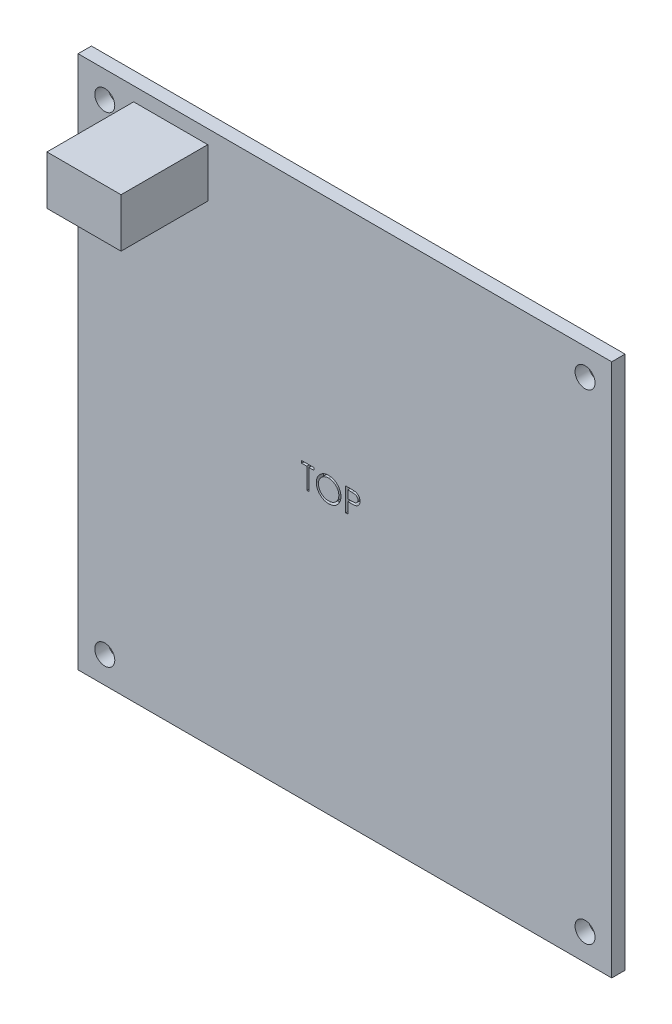
SolidWorks part; units mm, degrees
material "Epoxy, renforcé"
ref_plane "Plan de face" through (0, 0, 0) normal (0, 0, 1) x (1, 0, 0)
ref_plane "Plan de dessus" through (0, 0, 0) normal (0, 1, 0) x (1, 0, 0)
ref_plane "Plan de droite" through (0, 0, 0) normal (1, 0, 0) x (0, 0, -1)
sketch "Esquisse1" plane through (0, 0, 0) normal (0, 0, 1) x (1, 0, 0)
  line L0 (40, 80) -> (40, 0) construction
  line L1 (0, 0) -> (80, 0)
  line L2 (0, 0) -> (0, 80)
  line L3 (0, 80) -> (80, 80)
  line L4 (80, 0) -> (80, 80)
  line L5 (0, 40) -> (80, 40) construction
  circle A0 centre (4, 76) radius 1.5
  circle A1 centre (76, 76) radius 1.5
  circle A2 centre (76, 4) radius 1.5
  circle A3 centre (4, 4) radius 1.5
  dimension "D5" = 3
  dimension "D1" = 80
  dimension "D2" = 80
  dimension "D3" = 4
  dimension "D4" = 4
extrude "Boss.-Extru.1" add sketch "Esquisse1" along normal blind 2
sketch "Esquisse5"
sketch "Esquisse2" plane through (0, 0, 2) normal (0, 0, 1) x (1, 0, 0)
  text T0 "TOP"
extrude "Enlèv. mat.-Extru.1" cut sketch "Esquisse2" against normal blind 1
sketch "Esquisse4" plane through (0, 0, 2) normal (0, 0, 1) x (1, 0, 0)
  line L1 (19.4401, 70.5813) -> (8.3305, 70.5813)
  line L2 (19.4401, 70.5813) -> (19.4401, 77.9135)
  line L3 (19.4401, 77.9135) -> (8.3305, 77.9135)
  line L4 (8.3305, 70.5813) -> (8.3305, 77.9135)
extrude "Boss.-Extru.2" add sketch "Esquisse4" along normal blind 13
